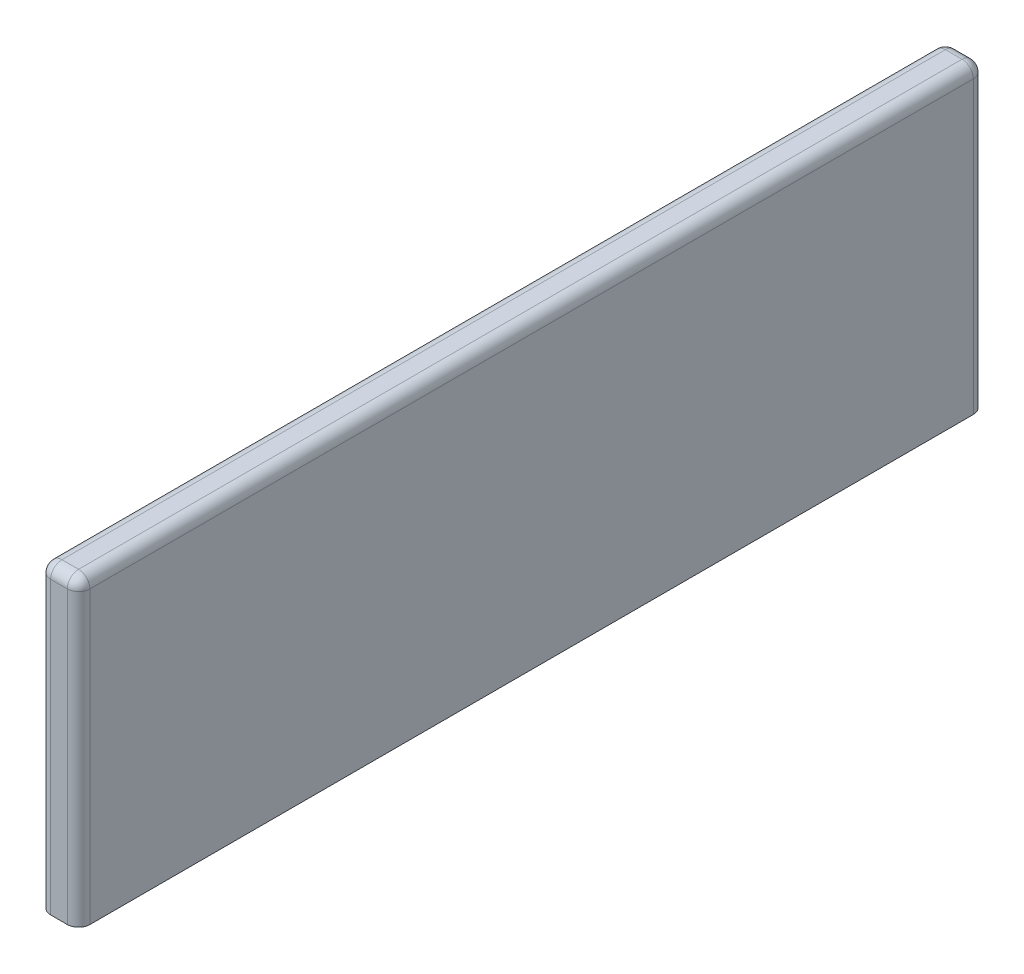
SolidWorks part; units mm, degrees
ref_plane "Piano frontale" through (0, 0, 0) normal (0, 0, 1) x (1, 0, 0)
ref_plane "Piano superiore" through (0, 0, 0) normal (0, 1, 0) x (1, 0, 0)
ref_plane "Piano destro" through (0, 0, 0) normal (1, 0, 0) x (0, 0, -1)
sketch "Schizzo2" plane through (0, 0, 0) normal (0, 0, 1) x (1, 0, 0)
  line L1 (0, 0) -> (-2.6, 0)
  line L2 (0, 0) -> (0, 20)
  line L3 (0, 20) -> (-2.6, 20)
  line L4 (-2.6, 0) -> (-2.6, 20)
  dimension "D1" = 2.6
  dimension "D2" = 20
extrude "Estrusione-Estrusione1" add sketch "Schizzo2" along normal blind 60
fillet "Raccordo1" radius 0.75 8 edges at (0, 20, 30) (-1.3, 20, 60) (-2.6, 20, 30) (-1.3, 20, 0) (0, 10, 60) (-2.6, 10, 60) (0, 10, 0) (-2.6, 10, 0)
